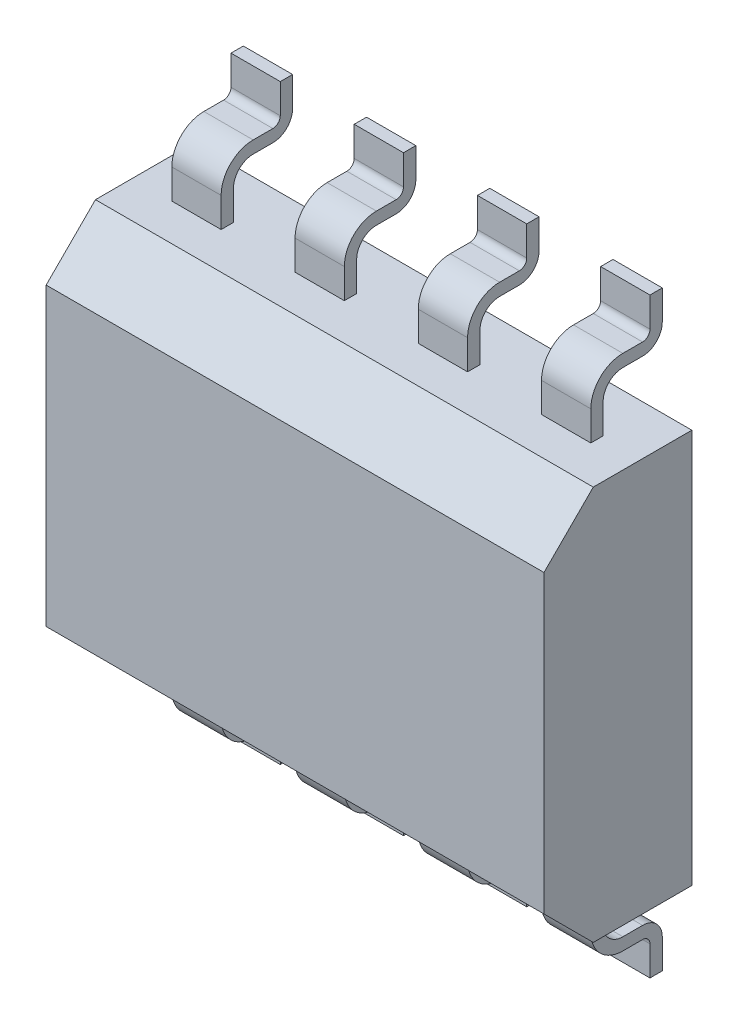
SolidWorks part; units mm, degrees
ref_plane "Front" through (0, 0, 0) normal (0, 0, 1) x (1, 0, 0)
ref_plane "Top" through (0, 0, 0) normal (0, 1, 0) x (1, 0, 0)
ref_plane "Right" through (0, 0, 0) normal (1, 0, 0) x (0, 0, -1)
sketch "Sketch1" plane through (0, 0, 0) normal (0, 0, 1) x (1, 0, 0)
  line L0 (2.525, 2) -> (-2.525, 2)
  line L1 (-2.525, 2) -> (-2.525, -2)
  line L2 (-2.525, -2) -> (2.525, -2)
  line L3 (2.525, -2) -> (2.525, 2)
  line L4 (-2.525, 0) -> (2.525, 0) construction
  dimension "D1" = 5.05
  dimension "D2" = 4
extrude "Extrude1" add sketch "Sketch1" along normal mid plane 1.5
chamfer "Chamfer1" distance 0.5 angle 45 2 edges at (0, -2, 0.75) (0, 2, 0.75)
sketch "Sketch2" plane through (0, 2, 0) normal (0, 1, 0) x (1, 0, 0)
  line L0 (2.125, 0.125) -> (2.125, 0.25)
  line L1 (1.625, 0.125) -> (2.125, 0.125)
  line L2 (1.625, 0.25) -> (1.625, 0.125)
  line L3 (2.125, 0.25) -> (1.625, 0.25)
  dimension "D1" = 0.125
  dimension "D2" = 0.5
  dimension "D3" = 1.625
  dimension "D4" = 0.125
ref_plane "Plane1" through (2.125, 0, 0) normal (1, 0, 0) x (0, 0, -1)
sketch "Sketch3" plane through (2.125, 0, 0) normal (1, 0, 0) x (0, 0, -1)
  line L0 (0.85, 2.7) -> (0.85, 3)
  line L1 (0.45, 2.5) -> (0.65, 2.5)
  line L2 (0.25, 2) -> (0.25, 2.3)
  arc A0 (0.65, 2.5) -> (0.85, 2.7) centre (0.65, 2.7) ccw
  arc A1 (0.45, 2.5) -> (0.25, 2.3) centre (0.45, 2.3) ccw
  dimension "D1" = 0.3
  dimension "D2" = 0.2
  dimension "D3" = 0.2
sweep "Sweep1" add profiles "Sketch2" path "Sketch3"
pattern_linear "LPattern1" count 4 spacing 1.25 along (-1, 0, 0) of "Sweep1"
mirror "Mirror1" about plane through (0, 0, 0) normal (0, 1, 0) of "LPattern1", "Sweep1"
